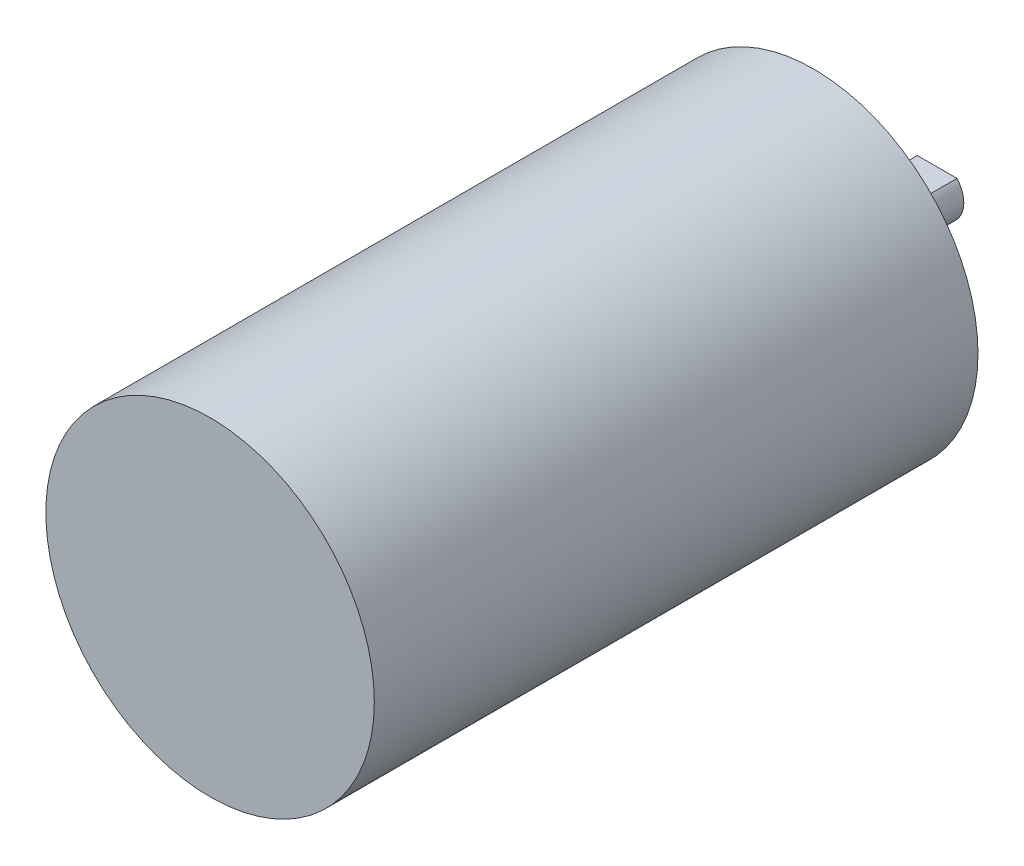
SolidWorks part; units mm, degrees
ref_plane "Front Plane" through (0, 0, 0) normal (0, 0, 1) x (1, 0, 0)
ref_plane "Top Plane" through (0, 0, 0) normal (0, 1, 0) x (1, 0, 0)
ref_plane "Right Plane" through (0, 0, 0) normal (1, 0, 0) x (0, 0, -1)
sketch "Sketch1" plane through (0, 0, 0) normal (0, 0, 1) x (1, 0, 0)
  circle A0 centre (0, 0) radius 18.5
  dimension "D1" = 37
extrude "Boss-Extrude1" add sketch "Sketch1" along normal blind 68
sketch "Sketch2" plane through (0, 0, 68) normal (0, 0, 1) x (1, 0, 0)
  point P0 (0, 0)
sketch "Sketch3" plane through (0, 0, 0) normal (0, 0, 1) x (1, 0, 0)
  circle A0 centre (0, 0) radius 6
  dimension "D1" = 12
extrude "Boss-Extrude2" add sketch "Sketch3" against normal blind 3.5
sketch "Sketch4" plane through (0, 0, -3.5) normal (0, 0, -1) x (-1, 0, 0)
  circle A0 centre (0, 0) radius 3
  dimension "D1" = 6
extrude "Boss-Extrude3" add sketch "Sketch4" along normal blind 10.4
sketch "Sketch5" plane through (0, 0, -13.9) normal (0, 0, -1) x (-1, 0, 0)
  line L0 (-2.2361, 2) -> (2.2361, 2)
  line L1 (0, 2) -> (0, 3) construction
  circle A0 centre (0, 0) radius 3 construction
  arc A1 (2.2361, 2) -> (-2.2361, 2) centre (0, 0) ccw
  dimension "D1" = 1
extrude "Cut-Extrude1" cut sketch "Sketch5" against normal blind 8
equation "\"MotorDIA\"= 37'ME 405 Motor Diameter"
equation "\"SyringeDIA\"= 31.4'60ml Syringe Diameter"
equation "\"MotorShaftDIA\"= 6'Motor Shaft Dia"
equation "\"MotorKeyway\"= 1'ME 405 Motor Shaft Keyway Depth"
equation "\"MotorLength\"= 67.5'ME 405 Motor Length Excluding Shaft"
equation "\"SyringeLength\"= 117.3'60ml Syringe Length Excluding Nozzle"
equation "\"3Dtol\"= .5'Sizing Tolerance for 3D printed parts"
equation "\"ChamberDIA\"= 100 - 4'Buoyancy Chamber inner Diameter"
equation "\"ChamberThk\"= 2mm'Buoyancy Chamber Wall Thickness"
equation "\"BearingOD\"= 10"
equation "\"BearingID\"= 4"
equation "\"Bearingwidth\"= 4"
equation "\"ShaftDIA\"= 4"
equation "\"D1@Sketch1\"=\"MotorDIA\""
